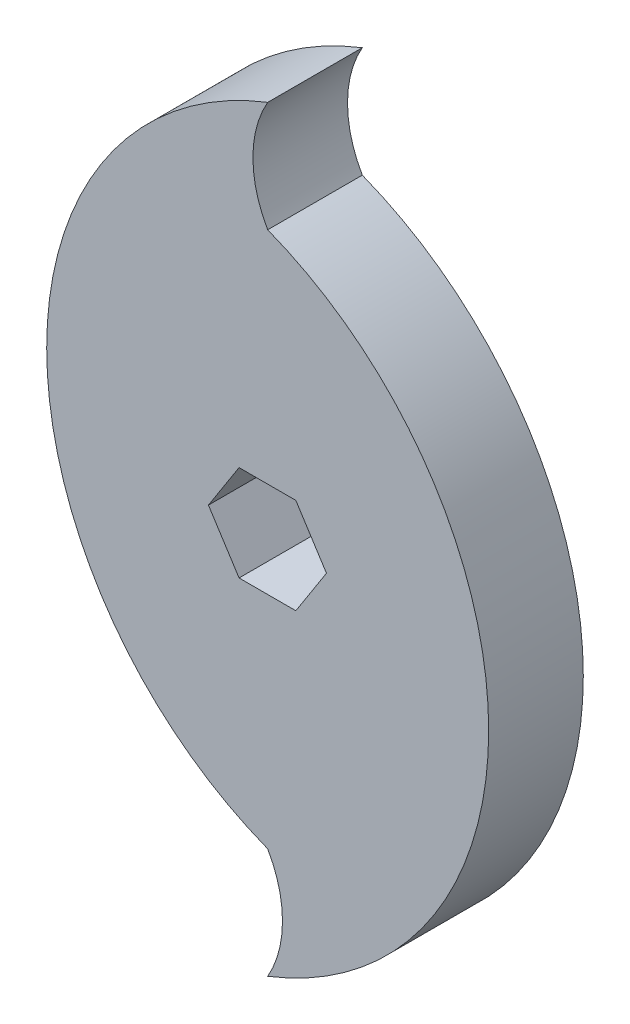
SolidWorks part; units mm, degrees
material "1.5805 (10NiCr5-4)"
ref_plane "Plan de face" through (0, 0, 0) normal (0, 0, 1) x (1, 0, 0)
ref_plane "Plan de dessus" through (0, 0, 0) normal (0, 1, 0) x (1, 0, 0)
ref_plane "Plan de droite" through (0, 0, 0) normal (1, 0, 0) x (0, 0, -1)
sketch "Esquisse1" plane through (0, 0, 0) normal (0, 0, 1) x (1, 0, 0)
  line L0 (0, 0) -> (0, -240) construction
  arc A0 (0, -205) -> (0, 0) centre (39.9218, -102.5) cw
  arc A1 (0, -35) -> (0, 0) centre (30.3109, -17.5) cw
  arc A2 (0, -205) -> (0, -240) centre (-30.3109, -222.5) cw
  arc A3 (0, -35) -> (0, -240) centre (-39.9218, -137.5) cw
  dimension "D3" = 35
  dimension "D4" = 110
  dimension "D6" = 35
  dimension "D5" = 35
  dimension "D7" = 110
  dimension "D1" = 240
  dimension "D2" = 35
extrude "Boss.-Extru.2" add sketch "Esquisse1" along normal blind 30
sketch "Esquisse3" plane through (0, 0, 30) normal (0, 0, 1) x (1, 0, 0)
  line L0 (-9.0782, -104.8464) -> (8.9218, -104.8464)
  line L1 (8.9218, -104.8464) -> (18.6361, -120)
  line L2 (18.6361, -120) -> (8.9218, -135.1536)
  line L3 (8.9218, -135.1536) -> (-9.0782, -135.1536)
  line L4 (-9.0782, -135.1536) -> (-18.7925, -120)
  line L5 (-18.7925, -120) -> (-9.0782, -104.8464)
  line L6 (-13.9354, -112.4232) -> (13.779, -127.5768) construction
  line L7 (-13.9354, -127.5768) -> (13.779, -112.4232) construction
  arc A2 (0, 0) -> (0, -205) centre (39.9218, -102.5) ccw construction
  point P8 (-0.0782, -120)
  dimension "D1" = 120
  dimension "D2" = 40
  dimension "D3" = 18
extrude "Enlèv. mat.-Extru.1" cut sketch "Esquisse3" against normal through all
